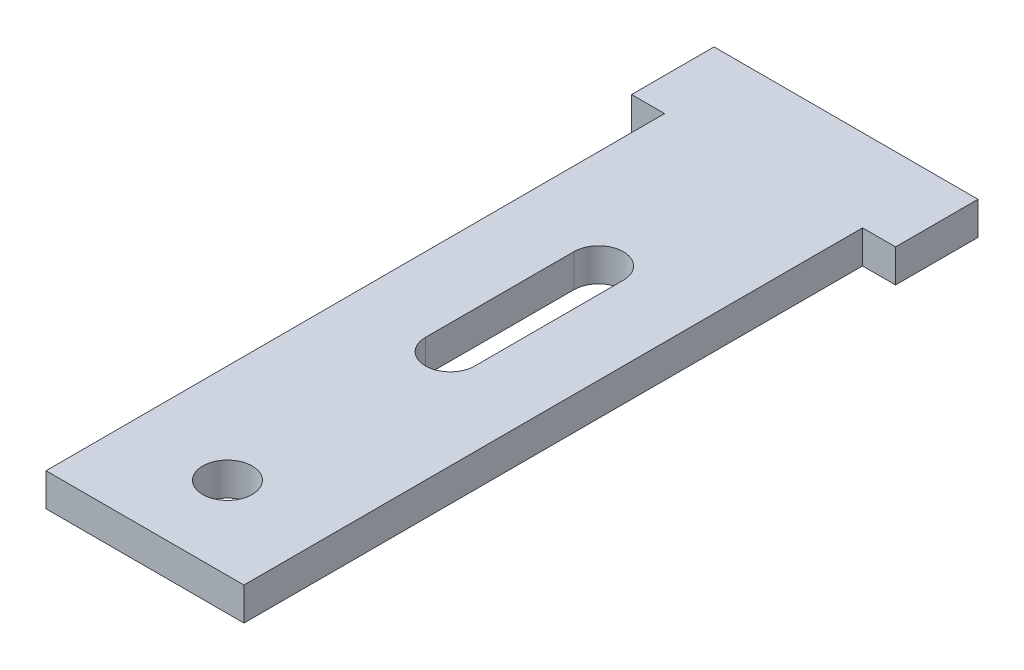
SolidWorks part; units mm, degrees
ref_plane "Front Plane" through (0, 0, 0) normal (0, 0, 1) x (1, 0, 0)
ref_plane "Top Plane" through (0, 0, 0) normal (0, 1, 0) x (1, 0, 0)
ref_plane "Right Plane" through (0, 0, 0) normal (1, 0, 0) x (0, 0, -1)
sketch "Sketch1" plane through (0, 0, 0) normal (0, 1, 0) x (1, 0, 0)
  line L0 (-6, 21.7357) -> (-8, 21.7357)
  line L1 (6, -15.7643) -> (-6, -15.7643)
  line L2 (6, -15.7643) -> (6, 21.7357)
  line L4 (-6, -15.7643) -> (-6, 21.7357)
  line L5 (-1.5, 2.7357) -> (1.5, 11.7357) construction
  line L7 (-8, 21.7357) -> (-8, 26.7357)
  line L8 (-8, 26.7357) -> (8, 26.7357)
  line L9 (8, 26.7357) -> (8, 21.7357)
  line L10 (8, 21.7357) -> (6, 21.7357)
  line L14 (1.5, 2.7357) -> (-1.5, 11.7357) construction
  line L16 (1.5, 2.7357) -> (1.5, 11.7357)
  line L18 (-1.5, 2.7357) -> (-1.5, 11.7357)
  line L19 (0, 26.7357) -> (0, -15.7643) construction
  line L20 (-1.5, 11.7357) -> (1.5, 11.7357) construction
  line L21 (-1.5, 2.7357) -> (1.5, 2.7357) construction
  line L22 (1.5, 7.2357) -> (-1.5, 7.2357) construction
  arc A5 (-1.5, 11.7357) -> (1.5, 11.7357) centre (0, 11.7357) cw
  arc A6 (-1.5, 2.7357) -> (1.5, 2.7357) centre (0, 2.7357) ccw
  circle A7 centre (0, -10.7643) radius 1.5
  point P0 (0, 0)
  point P14 (0, 7.2357)
  point P23 (0, 2.7357)
  dimension "D5" = 3
  dimension "D6" = 5
  dimension "D1" = 16
  dimension "D2" = 5
  dimension "D3" = 37.5
  dimension "D4" = 12
  dimension "D7" = 3
  dimension "D8" = 18
  dimension "D9" = 9
extrude "Boss-Extrude1" add sketch "Sketch1" along normal blind 2
